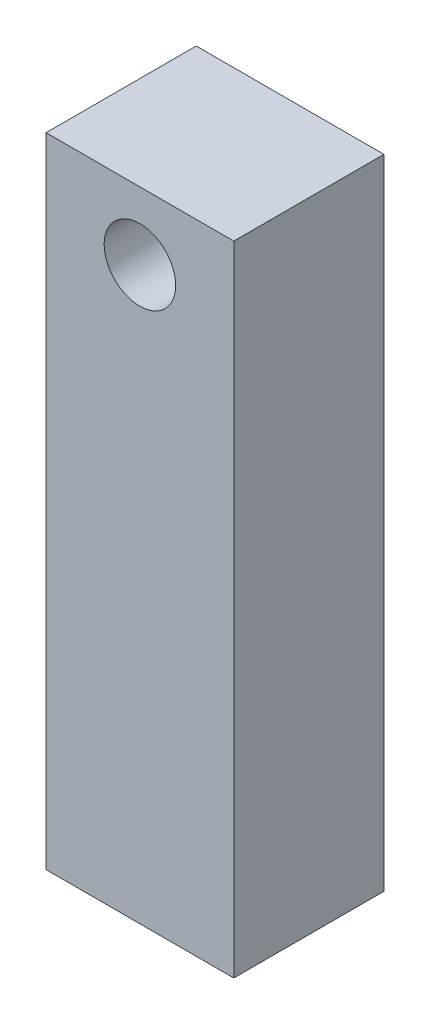
SolidWorks part; units mm, degrees
material "Plain Carbon Steel"
ref_plane "Front Plane" through (0, 0, 0) normal (0, 0, 1) x (1, 0, 0)
ref_plane "Top Plane" through (0, 0, 0) normal (0, 1, 0) x (1, 0, 0)
ref_plane "Right Plane" through (0, 0, 0) normal (1, 0, 0) x (0, 0, -1)
sketch "Sketch1" plane through (0, 0, 0) normal (0, 1, 0) x (1, 0, 0)
  line L0 (-12.5, -10) -> (12.5, -10)
  line L1 (12.5, -10) -> (12.5, 10)
  line L2 (12.5, 10) -> (-12.5, 10)
  line L3 (-12.5, 10) -> (-12.5, -10)
extrude "Boss-Extrude1" add sketch "Sketch1" along normal blind 85
sketch "Sketch2" plane through (0, 0, 0) normal (0, 0, 1) x (1, 0, 0)
  circle A0 centre (0, 76) radius 4.7625
  dimension "D1" = 9.525
extrude "Cut-Extrude1" cut sketch "Sketch2" against normal mid plane 24
